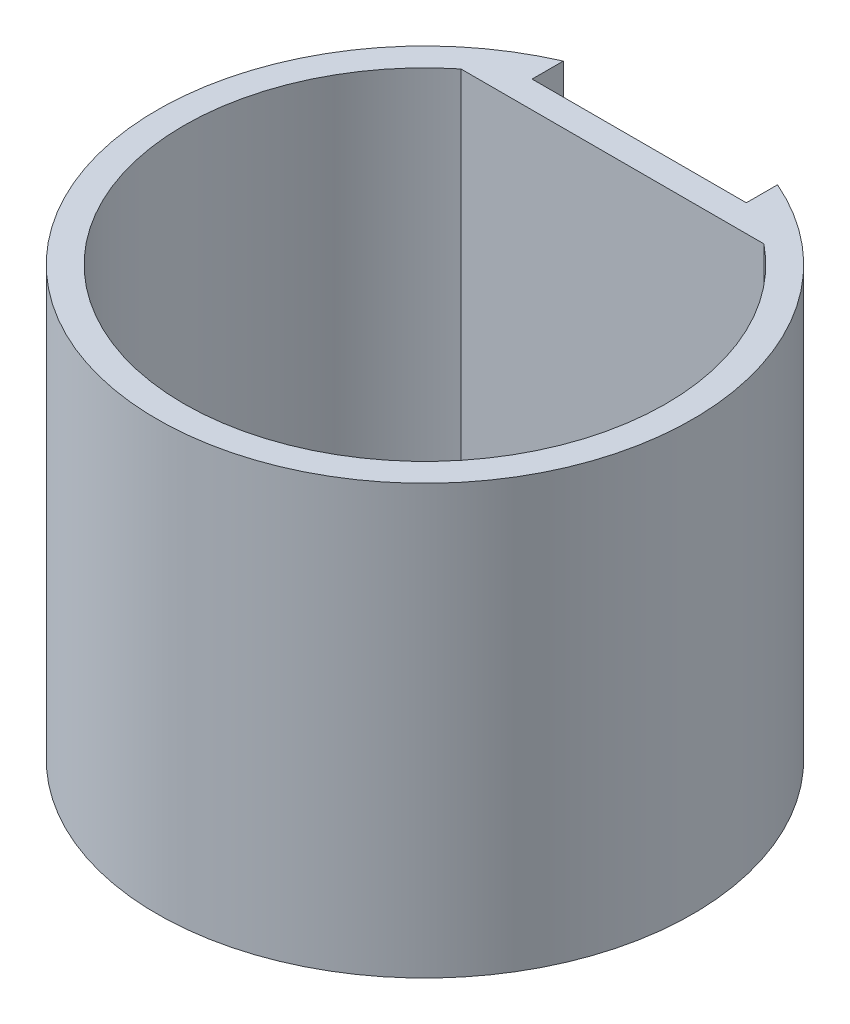
SolidWorks part; units mm, degrees
ref_plane "Front Plane" through (0, 0, 0) normal (0, 0, 1) x (1, 0, 0)
ref_plane "Top Plane" through (0, 0, 0) normal (0, 1, 0) x (1, 0, 0)
ref_plane "Right Plane" through (0, 0, 0) normal (1, 0, 0) x (0, 0, -1)
sketch "Sketch1" plane through (0, 0, 0) normal (0, 1, 0) x (1, 0, 0)
  line L0 (-64.2249, 0) -> (192.0292, 0) construction
  line L1 (-128.4498, 80) -> (198.8067, 80) construction
  line L2 (-40, 91.6515) -> (-40, 80)
  line L3 (-40, 80) -> (40, 80)
  line L4 (40, 80) -> (40, 91.6515)
  arc A0 (-40, 91.6515) -> (40, 91.6515) centre (0, 0) ccw
  point P10 (0, 80)
  dimension "D1" = 200
  dimension "D2" = 80
  dimension "D3" = 80
extrude "Boss-Extrude1" add sketch "Sketch1" against normal blind 160 contours L2 L3 L4 A0
sketch "Sketch2" plane through (0, 0, 0) normal (0, 1, 0) x (1, 0, 0)
  line L0 (-105.8596, 70) -> (178.1214, 70) construction
  line L1 (-50, 74.8331) -> (-50, 70)
  line L2 (-50, 70) -> (50, 70)
  line L3 (50, 70) -> (50, 74.8331)
  arc A0 (-50, 74.8331) -> (50, 74.8331) centre (0, 0) ccw
  point P7 (0, 70)
  dimension "D1" = 180
  dimension "D2" = 70
  dimension "D3" = 100
extrude "Cut-Extrude1" cut sketch "Sketch2" against normal blind 150 contours L0 A0 L2
